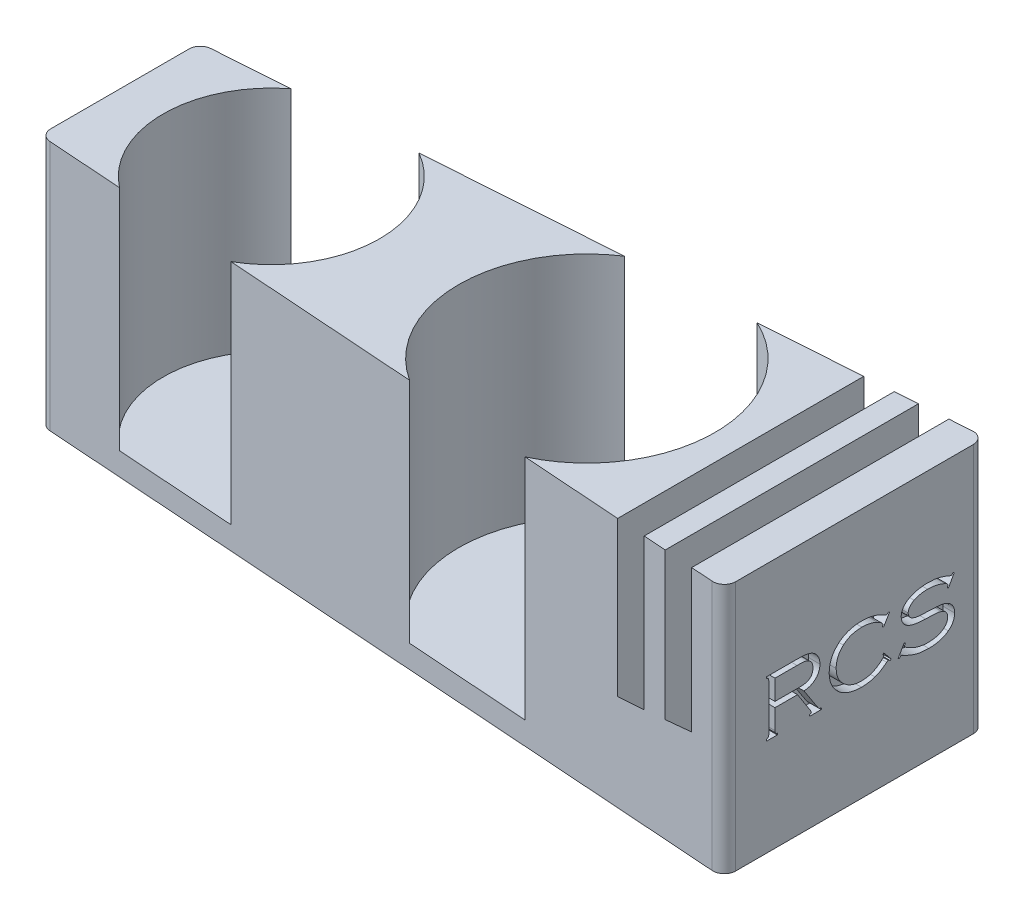
SolidWorks part; units mm, degrees
ref_plane "Front Plane" through (0, 0, 0) normal (0, 0, 1) x (1, 0, 0)
ref_plane "Top Plane" through (0, 0, 0) normal (0, 1, 0) x (1, 0, 0)
ref_plane "Right Plane" through (0, 0, 0) normal (1, 0, 0) x (0, 0, -1)
sketch "Sketch1" plane through (0, 0, 0) normal (0, 1, 0) x (1, 0, 0)
  line L0 (0, 7) -> (64.5, 11.5)
  line L1 (0, 7) -> (0, -7)
  line L2 (64.5, 11.5) -> (64.5, -11.5)
  line L3 (0, -7) -> (64.5, -11.5)
  line L4 (0, 7) -> (64.5, -11.5) construction
  line L5 (64.5, 11.5) -> (0, -7) construction
extrude "Boss-Extrude1" add sketch "Sketch1" along normal blind 2
sketch "Sketch2" plane through (0, 2, 0) normal (0, 1, 0) x (1, 0, 0)
  line L0 (61.5023, 11.2909) -> (61.4974, -11.2905)
  line L1 (64.5, 11.5) -> (0, 7) construction
  line L2 (0, -7) -> (64.5, -11.5) construction
  line L3 (61.4974, -11.2905) -> (64.5, -11.5)
  line L4 (64.5, -11.5) -> (64.5, 11.5)
  line L5 (64.5, 11.5) -> (61.5023, 11.2909)
extrude "Boss-Extrude2" add sketch "Sketch2" along normal blind 20 contours L0 L3 L4 L5
sketch "Sketch4" plane through (0, 2, 0) normal (0, 1, 0) x (1, 0, 0)
  line L0 (61.4974, -11.2905) -> (61.5023, 11.2909)
  line L1 (0, -7) -> (61.4974, -11.2905) construction
  line L2 (61.5023, 11.2909) -> (0, 7) construction
  line L3 (61.5023, 11.2909) -> (58.9952, 11.1159)
  line L4 (58.9952, 11.1159) -> (58.9952, -11.1159)
  line L5 (58.9952, -11.1159) -> (61.4974, -11.2905)
extrude "Boss-Extrude3" add sketch "Sketch4" along normal blind 20
sketch "Sketch5" plane through (58.9952, 0, 0) normal (-1, 0, 0) x (0, 0, 1)
  circle A0 centre (0, 14.2529) radius 12.25
extrude "Cut-Extrude1" cut sketch "Sketch5" against normal blind 2.5
sketch "Sketch6" plane through (61.4952, 0, 0) normal (-1, 0, 0) x (0, 0, 1)
  line L1 (-11.2904, 9.5) -> (11.2904, 9.5)
  line L2 (-11.2904, 9.5) -> (-11.2904, 22)
  line L3 (-11.2904, 22) -> (11.2904, 22)
  line L4 (11.2904, 9.5) -> (11.2904, 22)
  line L5 (11.2904, 9.5) -> (11.2904, 19.0058) construction
extrude "Cut-Extrude3" cut sketch "Sketch6" along normal blind 2.5
sketch "Sketch8" plane through (0, 2, 0) normal (0, 1, 0) x (1, 0, 0)
  line L0 (58.9952, 11.1159) -> (57.0066, 10.9772)
  line L1 (58.9952, 11.1159) -> (0, 7) construction
  line L2 (57.0066, 10.9772) -> (57.0066, -10.9772)
  line L3 (0, -7) -> (58.9952, -11.1159) construction
  line L4 (57.0066, -10.9772) -> (58.9952, -11.1159)
  line L5 (58.9952, -11.1159) -> (58.9952, 11.1159)
extrude "Boss-Extrude4" add sketch "Sketch8" along normal blind 20
sketch "Sketch9" plane through (0, 2, 0) normal (0, 1, 0) x (1, 0, 0)
  line L0 (57.0066, 10.9772) -> (54.5089, 10.8029)
  line L1 (57.0066, 10.9772) -> (0, 7) construction
  line L2 (54.5089, 10.8029) -> (54.5089, -10.8029)
  line L3 (0, -7) -> (57.0066, -10.9772) construction
  line L4 (54.5089, -10.8029) -> (57.0066, -10.9772)
  line L5 (57.0066, -10.9772) -> (57.0066, 10.9772)
extrude "Boss-Extrude5" add sketch "Sketch9" along normal blind 20
sketch "Sketch10" plane through (54.5089, 0, 0.0001) normal (-1, 0, 0) x (0, 0, 1)
  circle A0 centre (0, 14.224) radius 12.25
extrude "Cut-Extrude4" cut sketch "Sketch10" against normal blind 2.5
sketch "Sketch11" plane through (57.0089, 0, 0.0001) normal (-1, 0, 0) x (0, 0, 1)
  line L0 (-10.9774, 8.7872) -> (-10.9774, 22)
  line L1 (-10.9774, 22) -> (11.0716, 22)
  line L2 (11.0716, 22) -> (10.9773, 8.787)
  line L3 (10.9773, 8.787) -> (-10.9774, 8.7872)
  line L4 (10.8029, 22) -> (11.1159, 22) construction
extrude "Cut-Extrude5" cut sketch "Sketch11" along normal blind 2.5
sketch "Sketch12" plane through (0, 2, 0) normal (0, 1, 0) x (1, 0, 0)
  line L0 (54.5089, 10.8029) -> (0, 7)
  line L1 (0, 7) -> (0, -7)
  line L2 (0, -7) -> (54.5089, -10.8029)
  line L3 (54.5089, -10.8029) -> (54.5089, 10.8029)
  line L5 (54.5089, 10.8029) -> (0, 7) construction
extrude "Boss-Extrude6" add sketch "Sketch12" along normal blind 20
sketch "Sketch13" plane through (0, 22, 0) normal (0, 1, 0) x (1, 0, 0)
  circle A0 centre (13.3, 0) radius 9.5
extrude "Cut-Extrude6" cut sketch "Sketch13" against normal blind 20
sketch "Sketch14" plane through (0, 22, 0) normal (0, 1, 0) x (1, 0, 0)
  circle A0 centre (41, 0) radius 11.25
extrude "Cut-Extrude7" cut sketch "Sketch14" against normal blind 20
sketch "Sketch15" plane through (64.5, 0, 0) normal (1, 0, 0) x (0, 0, -1)
  text T0 "RCS" font "Copperplate Gothic Light" height in points 24
extrude "Cut-Extrude8" cut sketch "Sketch15" against normal blind 1
fillet "Fillet2" radius 1 4 edges at (0, 11, -7) (0, 11, 7) (64.5, 11, -11.5) (64.5, 11, 11.5)
